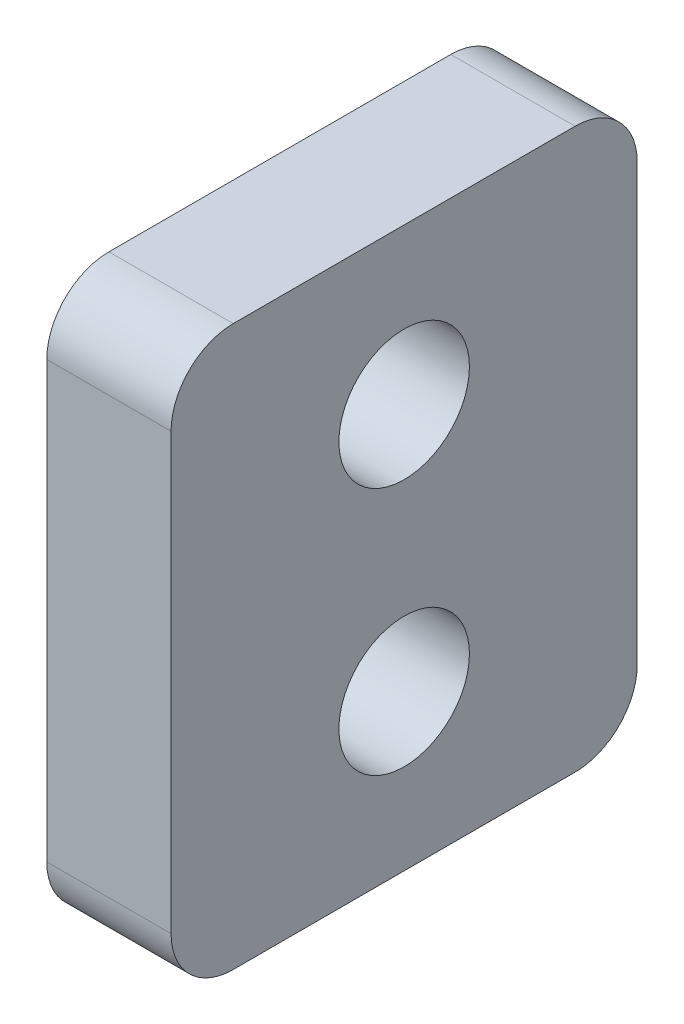
SolidWorks part; units mm, degrees
ref_plane "Front Plane" through (0, 0, 0) normal (0, 0, 1) x (1, 0, 0)
ref_plane "Top Plane" through (0, 0, 0) normal (0, 1, 0) x (1, 0, 0)
ref_plane "Right Plane" through (0, 0, 0) normal (1, 0, 0) x (0, 0, -1)
sketch "Sketch4" plane through (0, 0, 0) normal (1, 0, 0) x (0, 0, -1)
  line L0 (-7.5, 0) -> (7.5, 0) construction
  line L1 (-7.5, -9) -> (7.5, -9)
  line L2 (-7.5, -9) -> (-7.5, 9)
  line L3 (-7.5, 9) -> (7.5, 9)
  line L4 (7.5, -9) -> (7.5, 9)
  line L5 (-7.5, -9) -> (7.5, 9) construction
  line L6 (-7.5, 9) -> (7.5, -9) construction
  line L7 (0, 4) -> (0, -4) construction
  circle A0 centre (0, 4) radius 2.1
  circle A1 centre (0, -4) radius 2.1
  point P0 (0, 0)
  dimension "D3" = 8
  dimension "D4" = 4.2
  dimension "D1" = 18
  dimension "D2" = 15
extrude "Boss-Extrude1" add sketch "Sketch4" along normal blind 4
fillet "Fillet1" radius 2 4 edges at (2, -9, -7.5) (2, -9, 7.5) (2, 9, -7.5) (2, 9, 7.5)
